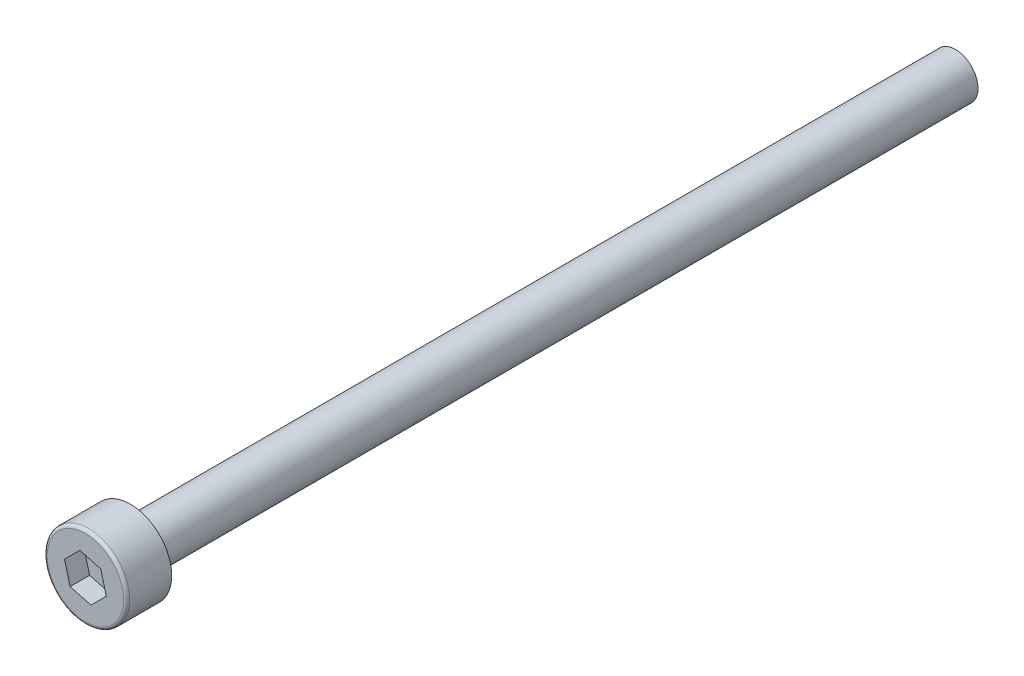
SolidWorks part; units mm, degrees
ref_plane "前视基准面" through (0, 0, 0) normal (0, 0, 1) x (1, 0, 0)
ref_plane "上视基准面" through (0, 0, 0) normal (0, 1, 0) x (1, 0, 0)
ref_plane "右视基准面" through (0, 0, 0) normal (1, 0, 0) x (0, 0, -1)
sketch "草图1" plane through (0, 0, 0) normal (0, 0, 1) x (1, 0, 0)
  circle A0 centre (0, 0) radius 2.75
  dimension "D1" = 5.5
extrude "凸台-拉伸1" add sketch "草图1" along normal blind 3
sketch "草图2" plane through (0, 0, 3) normal (0, 0, 1) x (1, 0, 0)
  line L1 (-1.0206, -1.0206) -> (0.3736, -1.3942)
  line L2 (0.3736, -1.3942) -> (1.3942, -0.3736)
  line L3 (1.3942, -0.3736) -> (1.0206, 1.0206)
  line L4 (1.0206, 1.0206) -> (-0.3736, 1.3942)
  line L5 (-0.3736, 1.3942) -> (-1.3942, 0.3736)
  line L6 (-1.3942, 0.3736) -> (-1.0206, -1.0206)
  circle A0 centre (0, 0) radius 1.25 construction
  dimension "D1" = 2.5
extrude "切除-拉伸1" cut sketch "草图2" against normal blind 1.3
sketch "草图3" plane through (0, 0, 0) normal (0, 0, -1) x (-1, 0, 0)
  circle A0 centre (0, 0) radius 1.5
  dimension "D1" = 3
extrude "凸台-拉伸2" add sketch "草图3" along normal blind 55
fillet "圆角1" radius 0.2 1 edges at (2.75, 0, 3)
